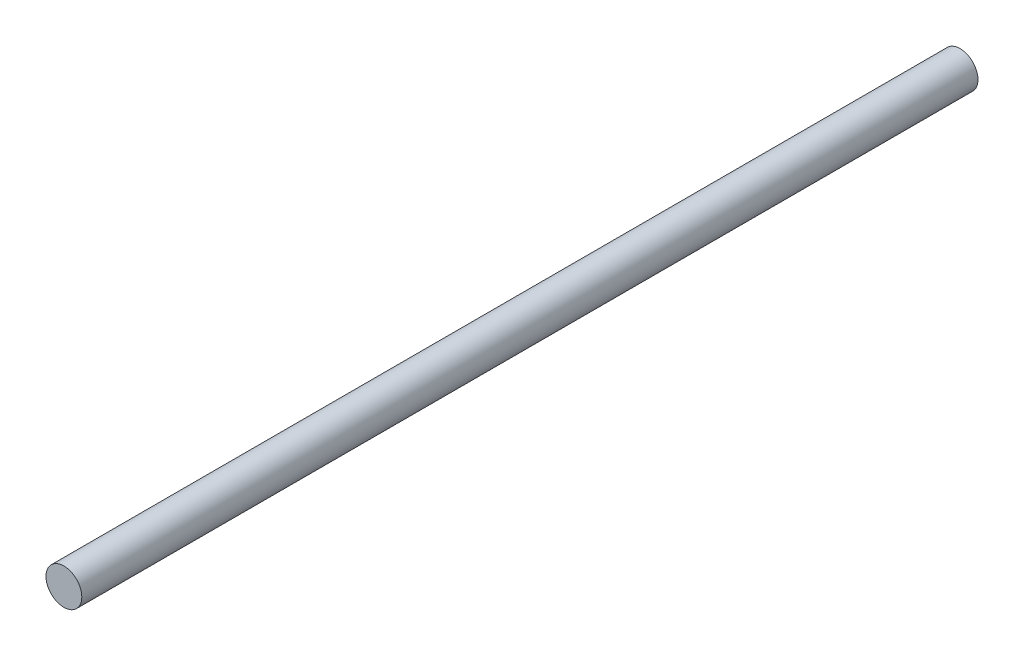
SolidWorks part; units mm, degrees
ref_plane "Plan de face" through (0, 0, 0) normal (0, 0, 1) x (1, 0, 0)
ref_plane "Plan de dessus" through (0, 0, 0) normal (0, 1, 0) x (1, 0, 0)
ref_plane "Plan de droite" through (0, 0, 0) normal (1, 0, 0) x (0, 0, -1)
sketch "Esquisse1" plane through (0, 0, 0) normal (0, 0, 1) x (1, 0, 0)
  circle A0 centre (0, 0) radius 2
  dimension "D1" = 4
extrude "Boss.-Extru.1" add sketch "Esquisse1" along normal blind 100
